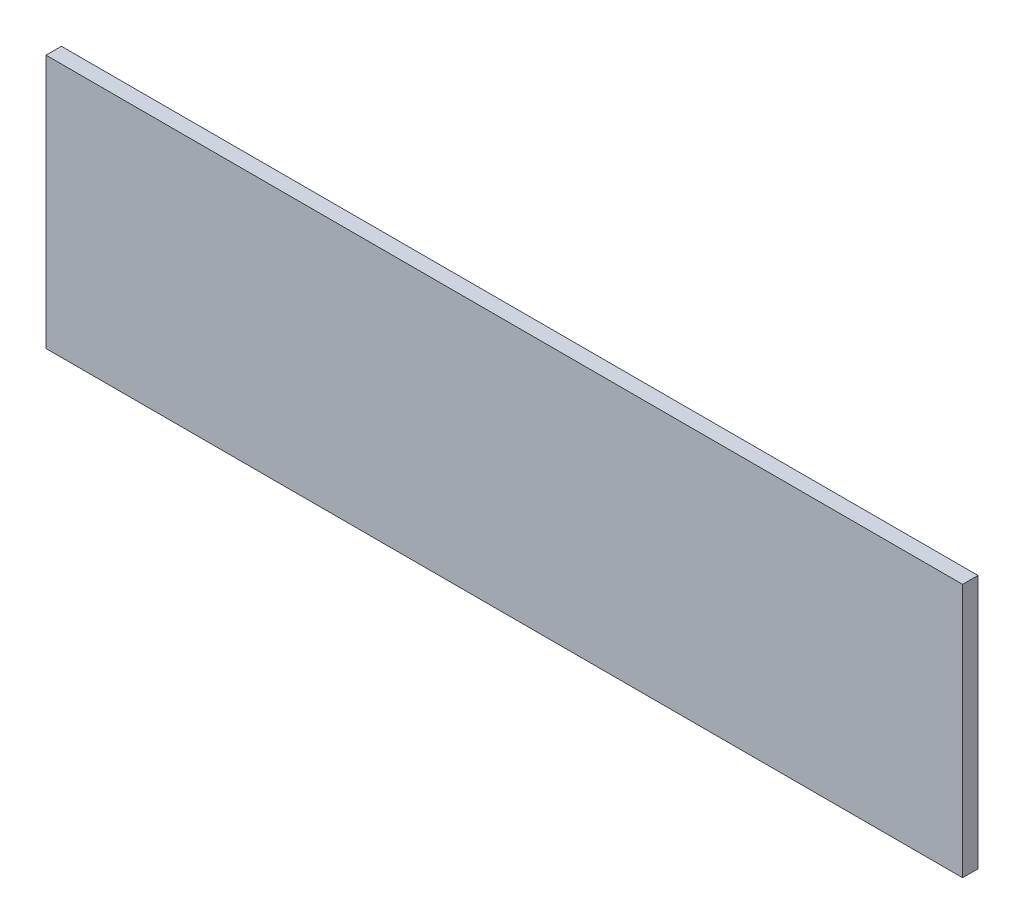
SolidWorks part; units mm, degrees
ref_plane "Plan de face" through (0, 0, 0) normal (0, 0, 1) x (1, 0, 0)
ref_plane "Plan de dessus" through (0, 0, 0) normal (0, 1, 0) x (1, 0, 0)
ref_plane "Plan de droite" through (0, 0, 0) normal (1, 0, 0) x (0, 0, -1)
sketch "Esquisse1" plane through (0, 0, 0) normal (0, 0, 1) x (1, 0, 0)
  line L1 (-148.75, -41.235) -> (148.75, -41.235)
  line L2 (-148.75, -41.235) -> (-148.75, 41.235)
  line L3 (-148.75, 41.235) -> (148.75, 41.235)
  line L4 (148.75, -41.235) -> (148.75, 41.235)
  line L5 (-148.75, -41.235) -> (148.75, 41.235) construction
  line L6 (-148.75, 41.235) -> (148.75, -41.235) construction
  point P0 (0, 0)
  dimension "D1" = 297.5
  dimension "D2" = 82.47
extrude "Boss.-Extru.1" add sketch "Esquisse1" along normal blind 5
